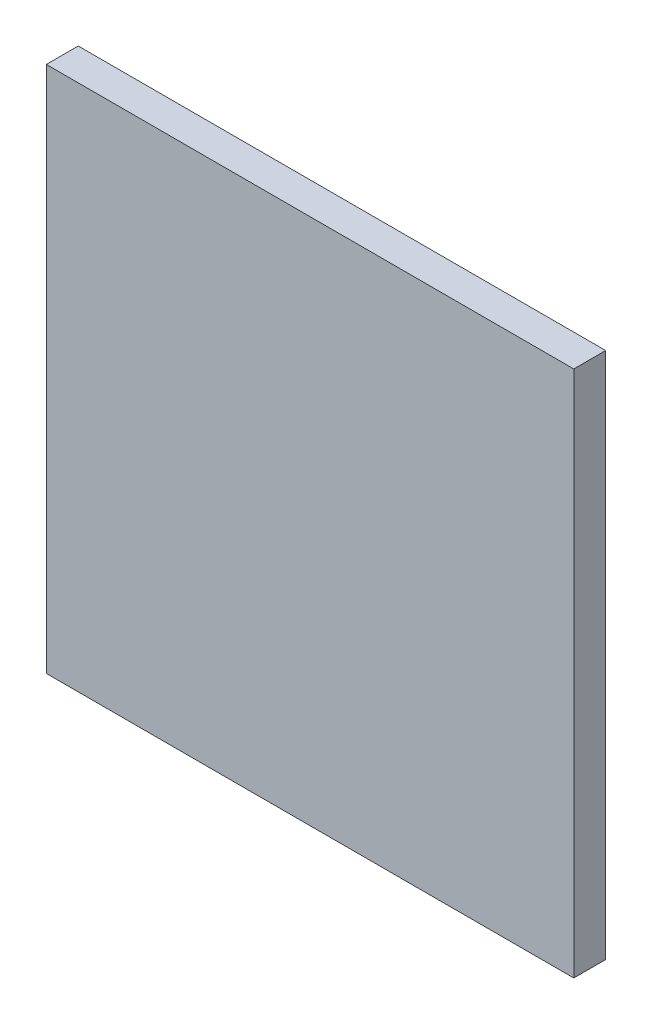
SolidWorks part; units mm, degrees
ref_plane "Front Plane" through (0, 0, 0) normal (0, 0, 1) x (1, 0, 0)
ref_plane "Top Plane" through (0, 0, 0) normal (0, 1, 0) x (1, 0, 0)
ref_plane "Right Plane" through (0, 0, 0) normal (1, 0, 0) x (0, 0, -1)
sketch "Sketch1" plane through (0, 0, 0) normal (0, 0, 1) x (1, 0, 0)
  line L1 (-3.15, -3.15) -> (3.15, -3.15)
  line L2 (-3.15, -3.15) -> (-3.15, 3.15)
  line L3 (-3.15, 3.15) -> (3.15, 3.15)
  line L4 (3.15, -3.15) -> (3.15, 3.15)
  line L5 (-3.15, -3.15) -> (3.15, 3.15) construction
  line L6 (-3.15, 3.15) -> (3.15, -3.15) construction
  point P0 (0, 0)
  dimension "D1" = 6.3
  dimension "D2" = 6.3
extrude "chip" add sketch "Sketch1" along normal blind 0.381
equation "\"pcb_length\"= 26.0\t' length of the chip in the direction of the feadline"
equation "\"pcb_side\"= 10   \t' length of the chip in the other direction"
equation "\"pcb_width\"= 0.381\t' thickness of the PCB (381 um)"
equation "\"wall_width\"= 1 \t' minimal width from the box walls"
equation "\"route_width\"= 0.5\t' The width of the trace on the lid for not touching the signal roates."
equation "\"route_clearence\"= 0.04\t' The clearence depth of the trace on the lid for not touching the signal roates."
equation "\"route_chip_clearence\"= 0"
equation "\"port_count\"= 2"
equation "\"port_space\"= 1.5"
equation "\"port_length\"= 5.1"
equation "\"port_width\"= 5.1"
equation "\"chip_length\"= 6.3\t' length of the chip in the direction of the feadline"
equation "\"chip_side\"= 6.3\t' length of the chip in the other direction"
equation "\"chip_width\"= 0.381\t' thickness of the chip (381 um)"
equation "\"pedestal_depth\"= 0.0\t' depth of the pedestal under the chip"
equation "\"chip_leg\"= 0.8 \t' size of the legs the chip lay on in case there is pedestal"
equation "\"wing_length\"= 5\t' Mounting wing size"
equation "\"wing_width\"= 1\t' mounting wing width"
equation "\"bonding_clearence\"= 1"
equation "\"box_height\"= \"wall_width\" + \"pedestal_depth\" + \"pcb_width\""
equation "\"box_length\"= \"pcb_length\" + 2 * \"wall_width\""
equation "\"box_side\"= \"pcb_side\" + 2 * \"wall_width\""
equation "\"D1@Sketch1\"=\"chip_length\""
equation "\"D2@Sketch1\"=\"chip_side\""
equation "\"D1@chip\" = \"chip_width\""
